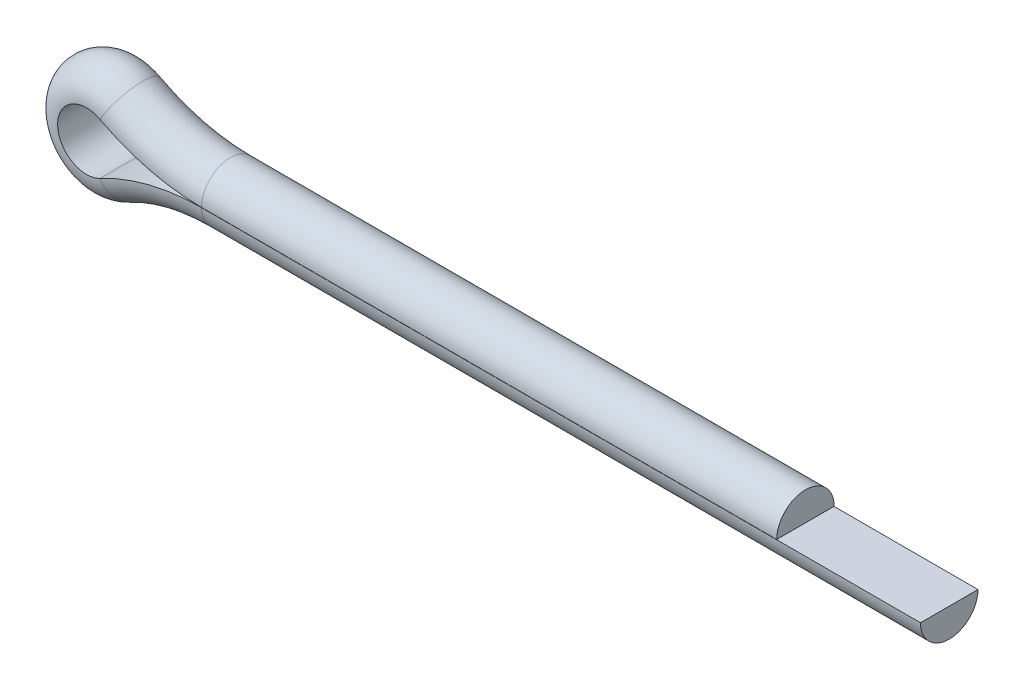
SolidWorks part; units mm, degrees
ref_plane "Front" through (0, 0, 0) normal (0, 0, 1) x (1, 0, 0)
ref_plane "Top" through (0, 0, 0) normal (0, 1, 0) x (1, 0, 0)
ref_plane "Right" through (0, 0, 0) normal (1, 0, 0) x (0, 0, -1)
sketch "PathSke" plane through (0, 0, 0) normal (0, 0, 1) x (1, 0, 0)
  line L0 (10, 0.5) -> (0, 0.5)
  line L1 (0, -0.5) -> (12.5, -0.5)
  line L2 (0, 0) -> (49.7718, 0) construction
  line L3 (0, 0) -> (0, 16.5256) construction
  line L4 (-3, 0) -> (-3, 13.5887) construction
  arc A0 (0, 0.5) -> (-1.5294, 0.8824) centre (0, 3.75) cw
  arc A1 (-1.5294, 0.8824) -> (-1.5294, -0.8824) centre (-2, 0) ccw
  arc A2 (-1.5294, -0.8824) -> (0, -0.5) centre (0, -3.75) cw
  dimension "Head_dia" = 2
  dimension "Diameter" = 1
  dimension "Head_ht" = 3
  dimension "Length" = 10
  dimension "Tip_offset" = 2.5
ref_plane "SectionPlane" through (10, 0, 0) normal (1, 0, 0) x (0, 0, -1)
sketch "SectionSke" plane through (10, 0, 0) normal (1, 0, 0) x (0, 0, -1)
  line L1 (-0.5, 0.002) -> (0.5, 0.002)
  arc A0 (0.5, 0.002) -> (-0.5, 0.002) centre (0, 0) ccw
  dimension "D1" = 0.002
  dimension "Diameter" = 1
sweep "Body" add profiles "SectionSke" path "PathSke"
sketch "ConeCutSke" plane through (0, 0, 0) normal (0, 0, 1) x (1, 0, 0)
  line L0 (0, 0) -> (0, 16.2682) construction
  line L1 (0, 0) -> (75.9079, 0) construction
  line L2 (0, 0) -> (12.5, 0) construction
  line L3 (10, 0.251) -> (9.6386, 0.51)
  line L4 (10, 0.002) -> (10, 0.5) construction
  line L6 (10, 0.251) -> (9.633, 0)
  line L7 (12.5, -0.251) -> (12.133, 0)
  line L8 (12.5, -0.5) -> (12.5, -0.002) construction
  line L9 (12.5, -0.251) -> (12.1386, -0.51)
  line L10 (12.133, 0) -> (9.633, 0)
  line L11 (9.6386, 0.51) -> (12.51, 0.51)
  line L12 (12.51, 0.51) -> (12.51, -0.51)
  line L13 (12.51, -0.51) -> (12.1386, -0.51)
  line L14 (10, 0.5) -> (0, 0.5) construction
  dimension "D1" = 0.01
  dimension "D2" = 0.01
  dimension "D3" = 70
  dimension "D4" = 70
extrude "ConeCut" [suppressed] cut sketch "ConeCutSke" against normal through all and the other way through all
equation "' \"Diameter@PathSke\" = 9.5"
equation "' \"Head_dia@PathSke\" = 19"
equation "' \"Head_ht@PathSke\" = 20"
equation "' \"Tip_offset@PathSke\" = 6.3"
equation "' \"Length@PathSke\" = 45"
equation "' \"Diameter@PathSke\" = 1"
equation "' \"Head_dia@PathSke\" = 2"
equation "' \"Head_ht@PathSke\" = 3"
equation "' \"Tip_offset@PathSke\" = 2.5"
equation "' \"Length@PathSke\" = 8"
equation "' \"Diameter@PathSke\" = 0.5"
equation "' \"Head_dia@PathSke\" = 1"
equation "' \"Head_ht@PathSke\" = 2"
equation "' \"Tip_offset@PathSke\" = 1.6"
equation "' \"Length@PathSke\" = 4"
equation "\"Diameter@SectionSke\" = \"Diameter@PathSke\""
equation "\"Length@SectionPlane\" = \"Length@PathSke\""
